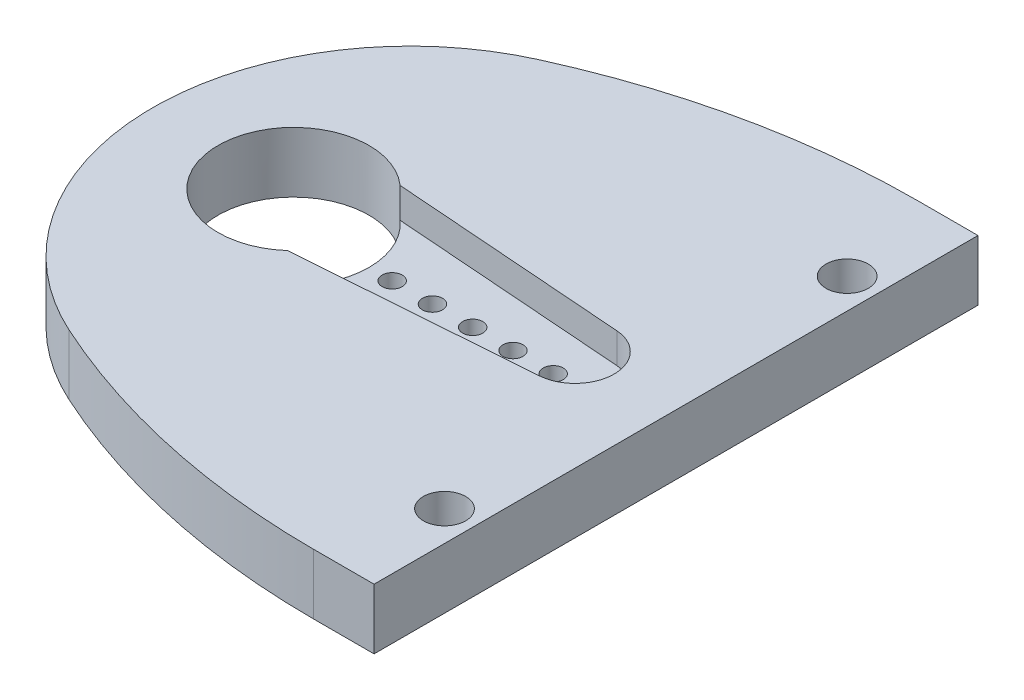
SolidWorks part; units mm, degrees
material "ABS"
ref_plane "Front Plane" through (0, 0, 0) normal (0, 0, 1) x (1, 0, 0)
ref_plane "Top Plane" through (0, 0, 0) normal (0, 1, 0) x (1, 0, 0)
ref_plane "Right Plane" through (0, 0, 0) normal (1, 0, 0) x (0, 0, -1)
sketch "Sketch1" plane through (0, 0, 0) normal (0, 1, 0) x (1, 0, 0)
  line L0 (0, 0) -> (11.2501, 0) construction
  line L1 (0.5, -11.6445) -> (0.5, 11.6445) construction
  line L12 (-7, 15) -> (19, 15)
  line L13 (-7, 15) -> (-7, -15)
  line L14 (-7, -15) -> (19, -15)
  line L15 (19, 15) -> (19, -15)
  line L16 (16, -15) -> (19, -15) construction
  line L17 (19, 15) -> (16, 15)
  line L18 (19, 15) -> (19, -15)
  line L19 (19, -15) -> (16, -15)
  line L20 (16, 15) -> (16, -15)
  line L21 (17.5, -15) -> (17.5, 15) construction
  circle A13 centre (0, 0) radius 2.35
  circle A14 centre (17.5, 10) radius 1.05
  circle A15 centre (17.5, -10) radius 1.05
  arc A16 (16, -15) -> (0.5, -11.6445) centre (16, 22.4771) cw
  arc A17 (16, 15) -> (0.5, 11.6445) centre (16, -22.4771) ccw
  arc A18 (0.5, 11.6445) -> (0.5, -11.6445) centre (5.7896, 0) ccw
  dimension "D4" = 30
  dimension "D6" = 17
  dimension "D5" = 2.1
  dimension "D13" = 20
  dimension "D3" = 2.1
  dimension "D2" = 4.7
  dimension "D10" = 26
  dimension "D11" = 7
  dimension "D12" = 3
extrude "Boss-Extrude1" add sketch "Sketch1" against normal blind 3
sketch "Esquisse1" plane through (0, 0, 0) normal (0, 1, 0) x (1, 0, 0)
  line L2 (2.4945, -2.8) -> (14.1314, -1.9323)
  line L3 (14.1314, 1.9323) -> (2.4945, 2.8)
  line L4 (2.4945, -2.8) -> (14.1314, -1.9323)
  line L5 (14.1314, 1.9323) -> (2.4945, 2.8)
  arc A1 (2.4945, 2.8) -> (2.4945, -2.8) centre (0, 0) ccw
  arc A2 (2.4945, 2.8) -> (2.4945, -2.8) centre (0, 0) ccw
  spline S1 degree 2 poles (-4686.9371, 16332.0334) (-102.0337, -57.9399) (14.8275, -1.7461) (15.1573, -1.5874) (15.4072, -1.3186) (15.6562, -1.0506) (15.7906, -0.7092) (15.9249, -0.3678) (15.925, 0) (15.9251, 0.3662) (15.791, 0.708) (15.6574, 1.0487) (15.4078, 1.3179) (15.1591, 1.5861) (14.8286, 1.7455) (-101.724, 57.9578) (-4813.7142, -16294.8363) knots -44.11303 -44.11303 -44.11303 0.125 0.125 0.25 0.25 0.375 0.375 0.5 0.5 0.625 0.625 0.75 0.75 0.875 0.875 45.001484 45.001484 45.001484 only from (14.1314, -1.9323) to (14.1314, 1.9323)
  spline S2 degree 2 poles (14.1314, -1.9323) (14.4973, -1.9048) (14.8275, -1.7461) (15.1573, -1.5874) (15.4072, -1.3186) (15.6562, -1.0506) (15.7906, -0.7092) (15.9249, -0.3678) (15.925, 0) (15.9251, 0.3662) (15.791, 0.708) (15.6574, 1.0487) (15.4078, 1.3179) (15.1591, 1.5861) (14.8286, 1.7455) (14.4984, 1.9047) (14.1314, 1.9323) knots 0 0 0 0.125 0.125 0.25 0.25 0.375 0.375 0.5 0.5 0.625 0.625 0.75 0.75 0.875 0.875 1 1 1
  dimension "D1" = 0
extrude "Enlèv. mat.-Extru.1" cut sketch "Esquisse1" against normal blind 1.5
sketch "Esquisse3" plane through (0, -1.5, 0) normal (0, 1, 0) x (1, 0, 0)
  circle A0 centre (4.9, 0) radius 0.5 construction
  circle A1 centre (6.9, 0) radius 0.5 construction
  circle A2 centre (8.9, 0) radius 0.5 construction
  circle A3 centre (10.9, 0) radius 0.5 construction
  circle A4 centre (12.9, 0) radius 0.5 construction
  circle A6 centre (4.9, 0) radius 0.5
  circle A7 centre (6.9, 0) radius 0.5
  circle A8 centre (8.9, 0) radius 0.5
  circle A9 centre (10.9, 0) radius 0.5
  circle A10 centre (12.9, 0) radius 0.5
  circle A11 centre (0, 0) radius 3.75
  arc A12 (2.4945, 2.8) -> (2.4945, -2.8) centre (0, 0) ccw construction
extrude "Enlèv. mat.-Extru.7" cut sketch "Esquisse3" against normal through all
